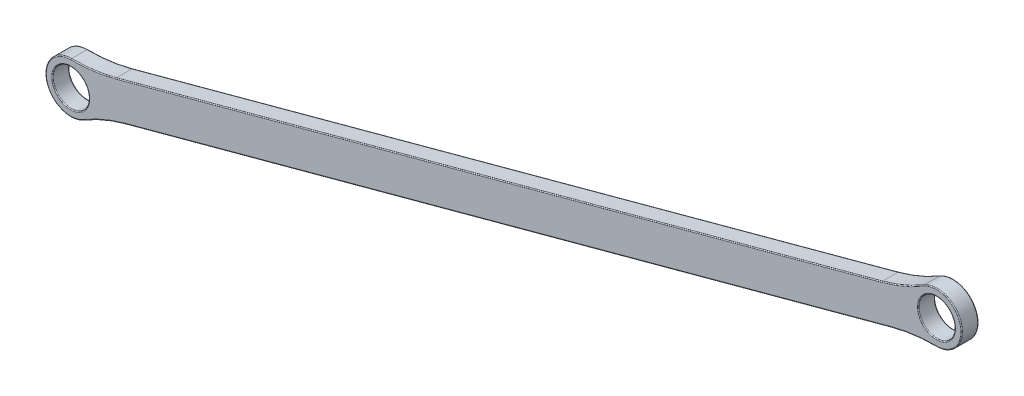
SolidWorks part; units mm, degrees
ref_plane "Front Plane" through (0, 0, 0) normal (0, 0, 1) x (1, 0, 0)
ref_plane "Top Plane" through (0, 0, 0) normal (0, 1, 0) x (1, 0, 0)
ref_plane "Right Plane" through (0, 0, 0) normal (1, 0, 0) x (0, 0, -1)
sketch "Sketch1" plane through (0, 0, 0) normal (0, 0, 1) x (1, 0, 0)
  line L0 (-59.1324, 229.7735) -> (-213.5959, 188.0481) construction
  line L1 (-59.1324, 229.7735) -> (-213.5959, 188.0481) construction
sketch "Sketch2" plane through (0, 0, 0) normal (0, 0, 1) x (1, 0, 0)
  line L0 (-59.1324, 229.7735) -> (-213.5959, 188.0481) construction
  line L1 (-59.1324, 229.7735) -> (-213.5959, 188.0481) construction
  line L2 (-58.2848, 226.6359) -> (-212.7484, 184.9105)
  line L3 (-59.9799, 232.911) -> (-214.4435, 191.1856)
  arc A0 (-58.2848, 226.6359) -> (-59.9799, 232.911) centre (-59.1324, 229.7735) ccw
  arc A1 (-214.4435, 191.1856) -> (-212.7484, 184.9105) centre (-213.5959, 188.0481) ccw
  circle A2 centre (-213.5959, 188.0481) radius 4.5
  circle A3 centre (-59.1324, 229.7735) radius 4.5
  arc A4 (-59.9799, 232.911) -> (-58.2848, 226.6359) centre (-59.1324, 229.7735) ccw
  arc A5 (-214.4435, 191.1856) -> (-212.7484, 184.9105) centre (-213.5959, 188.0481) cw
  point P5 (-136.3642, 208.9108)
  dimension "D2" = 9
  dimension "D3" = 9
  dimension "D1" = 6.5
extrude "Boss-Extrude1" add sketch "Sketch2" against normal blind 3 contours L2 A3 L3 A0 | L0 A4 L3 A3 | A4 L0 A3 L2 | L0 A3 L3 A2 | A3 L0 A2 L2 | L3 A2 L2 A1 | L0 A2 L3 A5 | A2 L0 A5 L2
fillet "Fillet1" radius 30 4 edges at (-62.9847, 232.0993, -1.5) (-61.2896, 225.8242, -1.5) (-209.7436, 185.7222, -1.5) (-211.4387, 191.9973, -1.5)
fillet "Fillet2" radius 0.15 20 edges at (-55.8824, 229.7735, -3) (-207.6912, 185.9939, -3) (-135.5166, 205.7732, -3) (-63.1996, 225.0255, -3) (-54.7881, 230.947, -3) (-65.0371, 231.8277, -3) (-137.2117, 212.0483, -3) (-209.5287, 192.796, -3) (-217.9402, 186.8745, -3) (-210.3459, 188.0481, -3) (-55.8824, 229.7735, 0) (-65.0371, 231.8277, 0) (-54.7881, 230.947, 0) (-63.1996, 225.0255, 0) (-135.5166, 205.7732, 0) (-207.6912, 185.9939, 0) (-217.9402, 186.8745, 0) (-209.5287, 192.796, 0) (-137.2117, 212.0483, 0) (-210.3459, 188.0481, 0)
